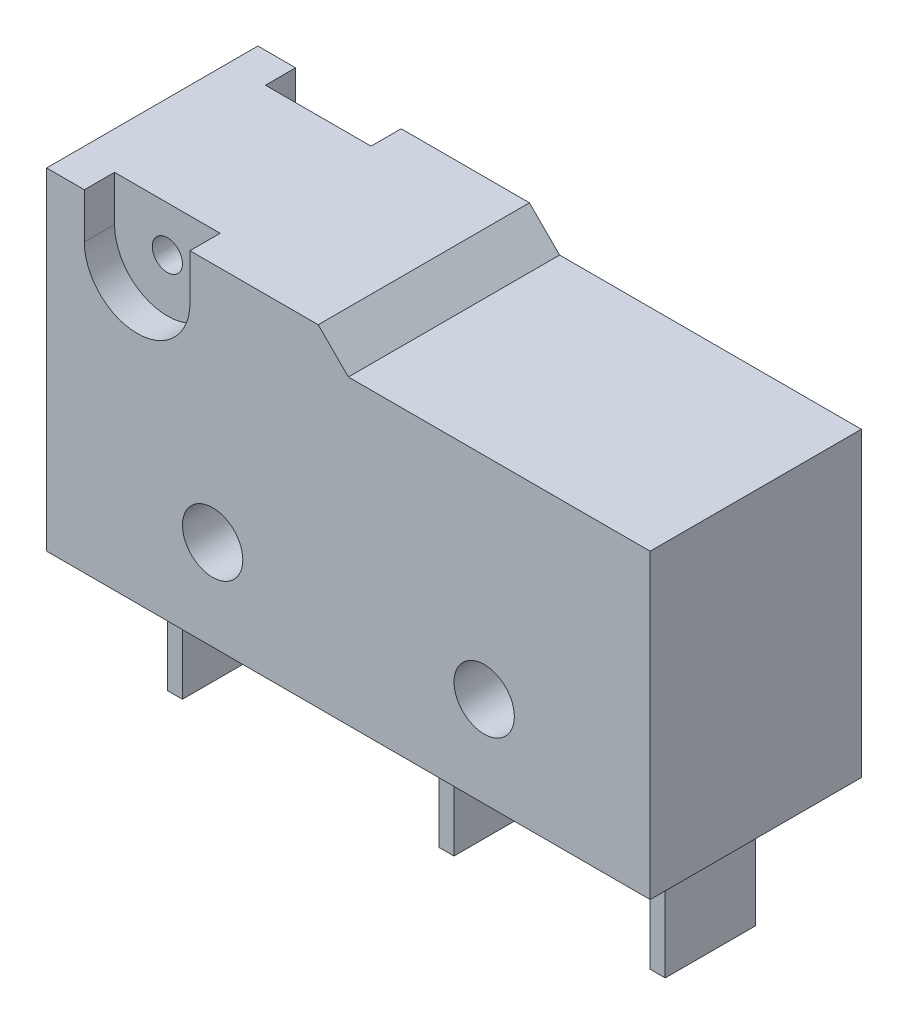
SolidWorks part; units mm, degrees
ref_plane "Plan de face" through (0, 0, 0) normal (0, 0, 1) x (1, 0, 0)
ref_plane "Plan de dessus" through (0, 0, 0) normal (0, 1, 0) x (1, 0, 0)
ref_plane "Plan de droite" through (0, 0, 0) normal (1, 0, 0) x (0, 0, -1)
sketch "Esquisse1" plane through (0, 0, 0) normal (0, 0, 1) x (1, 0, 0)
  line L1 (0, 0) -> (20, 0)
  line L2 (0, 0) -> (0, 11)
  line L3 (0, 11) -> (9, 11)
  line L4 (20, 0) -> (20, 10)
  line L6 (9, 11) -> (10, 10)
  line L7 (10, 10) -> (20, 10)
  circle A0 centre (3, 9.5) radius 0.5
  circle A1 centre (5.5, 3) radius 1
  circle A2 centre (14.5, 3) radius 1
  dimension "D6" = 3
  dimension "D7" = 2
  dimension "D8" = 7
  dimension "D9" = 4.5
  dimension "D10" = 4.5
  dimension "D11" = 9
  dimension "D12" = 3
  dimension "D13" = 9.5
  dimension "D14" = 1
  dimension "D1" = 10
  dimension "D2" = 20
  dimension "D3" = 11
  dimension "D4" = 135
  dimension "D5" = 10
extrude "Boss.-Extru.1" add sketch "Esquisse1" along normal mid plane 7
sketch "Esquisse2" plane through (0, 0, 0) normal (0, -1, 0) x (1, 0, 0)
  line L0 (0, 0) -> (2, 0) construction
  line L1 (2, 1.5) -> (2.5, 1.5)
  line L2 (2, 1.5) -> (2, -1.5)
  line L3 (2, -1.5) -> (2.5, -1.5)
  line L4 (2.5, 1.5) -> (2.5, -1.5)
  line L5 (11, 1.5) -> (11.5, 1.5)
  line L6 (11, 1.5) -> (11, -1.5)
  line L7 (11, -1.5) -> (11.5, -1.5)
  line L8 (11.5, 1.5) -> (11.5, -1.5)
  line L9 (18, -1.5) -> (18.5, -1.5)
  line L10 (18, -1.5) -> (18, 1.5)
  line L11 (18, 1.5) -> (18.5, 1.5)
  line L12 (18.5, -1.5) -> (18.5, 1.5)
  line L13 (0, 3.5) -> (0, -3.5) construction
  dimension "D1" = 2
  dimension "D2" = 0.5
  dimension "D3" = 11
  dimension "D4" = 18
  dimension "D5" = 3
extrude "Boss.-Extru.2" add sketch "Esquisse2" along normal blind 4 separate body
sketch "Esquisse3" plane through (0, 0, 3.5) normal (0, 0, 1) x (1, 0, 0)
  line L0 (3, 9.5) -> (3, 11) construction
  line L1 (9, 11) -> (0, 11) construction
  line L2 (1.25, 9.5) -> (1.25, 11)
  line L3 (4.75, 9.5) -> (4.75, 11)
  arc A0 (1.25, 9.5) -> (4.75, 9.5) centre (3, 9.5) ccw
  arc A1 (4.75, 11) -> (1.25, 11) centre (3, 11) ccw
  point P5 (3, 10.25)
  dimension "D1" = 3.5
extrude "Enlèv. mat.-Extru.1" cut sketch "Esquisse3" against normal blind 1
mirror "Symétrie1" about plane through (0, 0, 0) normal (0, 0, 1) of "Enlèv. mat.-Extru.1"
